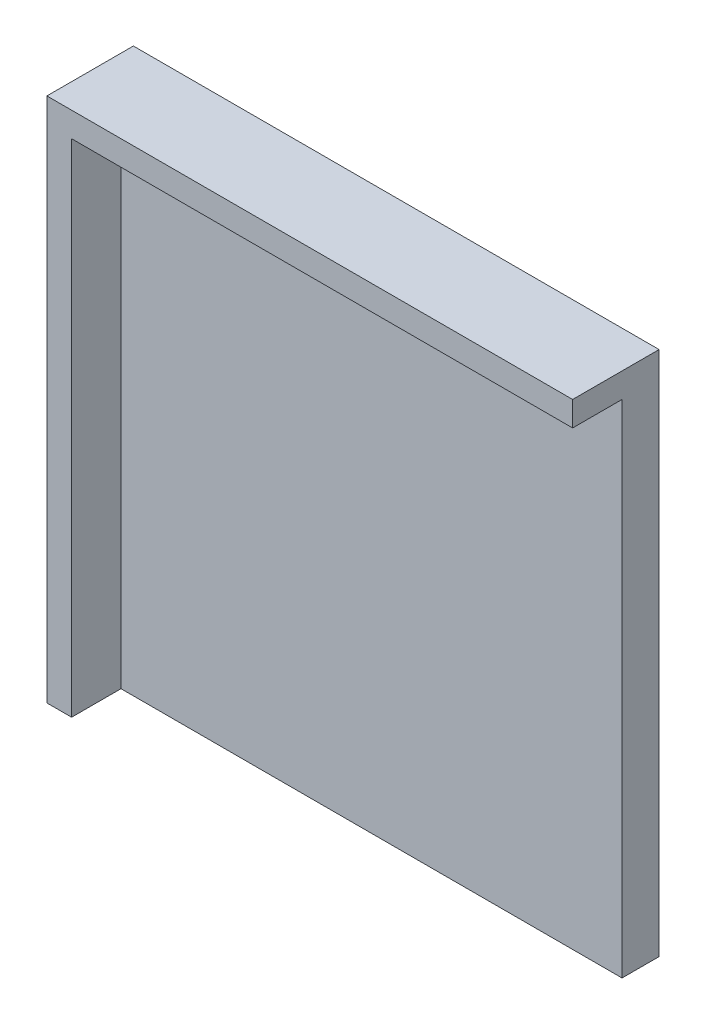
SolidWorks part; units mm, degrees
ref_plane "Front Plane" through (0, 0, 0) normal (1, 0, 0) x (0, 1, 0)
ref_plane "Top Plane" through (0, 0, 0) normal (0, 0, 1) x (0, 1, 0)
ref_plane "Right Plane" through (0, 0, 0) normal (0, 1, 0) x (-1, 0, 0)
sketch "Sketch1" plane through (0, 0, 0) normal (0, 0, 1) x (0, 1, 0)
  line L5 (-21.285, 21.285) -> (21.285, 21.285)
  line L6 (-21.285, 21.285) -> (-21.285, -21.285)
  line L7 (-21.285, -21.285) -> (21.285, -21.285)
  line L8 (21.285, 21.285) -> (21.285, -21.285)
  line L9 (-21.285, 21.285) -> (21.285, -21.285) construction
  line L10 (-21.285, -21.285) -> (21.285, 21.285) construction
  point P0 (0, 0)
  dimension "D1" = 42.57
  dimension "D2" = 42.57
extrude "Boss-Extrude1" add sketch "Sketch1" along normal blind 3
sketch "Sketch2" plane through (0, 0, 3) normal (0, 0, 1) x (1, 0, 0)
  line L0 (21.285, 21.285) -> (-21.285, 21.285)
  line L1 (-21.285, 21.285) -> (-21.285, -21.285)
  line L2 (-21.285, -21.285) -> (-19.285, -21.285)
  line L3 (21.285, -21.285) -> (-21.285, -21.285) construction
  line L4 (-19.285, -21.285) -> (-19.285, 19.285)
  line L5 (-19.285, 19.285) -> (21.285, 19.285)
  line L6 (21.285, 21.285) -> (21.285, -21.285) construction
  line L7 (21.285, 19.285) -> (21.285, 21.285)
  dimension "D1" = 2
  dimension "D2" = 2
extrude "Boss-Extrude2" add sketch "Sketch2" along normal blind 4
sketch "Sketch3" plane through (0, 0, 0) normal (0, 0, -1) x (1, 0, 0)
  line L0 (21.285, 21.285) -> (-21.285, -21.285) construction
  circle A0 centre (-14.2139, -14.2139) radius 2.1
  circle A1 centre (14.2139, 14.2139) radius 2.1
  dimension "D1" = 4.2
  dimension "D2" = 4.2
  dimension "D3" = 10
  dimension "D4" = 10
extrude "Cut-Extrude1" cut sketch "Sketch3" against normal blind 2
